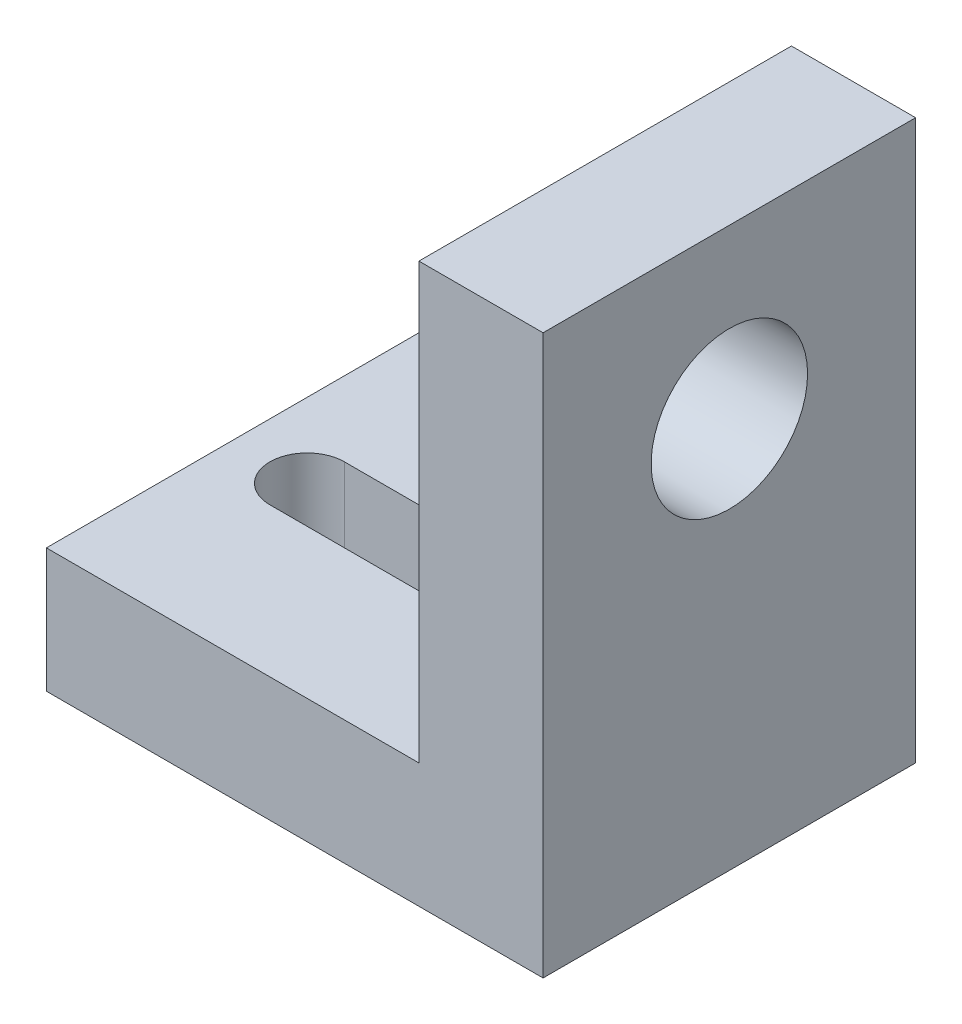
SolidWorks part; units mm, degrees
ref_plane "Front Plane" through (0, 0, 0) normal (0, 0, 1) x (1, 0, 0)
ref_plane "Top Plane" through (0, 0, 0) normal (0, 1, 0) x (1, 0, 0)
ref_plane "Right Plane" through (0, 0, 0) normal (1, 0, 0) x (0, 0, -1)
sketch "Croquis1" plane through (0, 0, 0) normal (0, 1, 0) x (1, 0, 0)
  line L0 (-10, -7.5) -> (10, -7.5)
  line L1 (-10, -7.5) -> (-10, 7.5)
  line L2 (10, -7.5) -> (10, 7.5)
  line L3 (-10, 7.5) -> (10, 7.5)
  line L4 (-10, -7.5) -> (10, 7.5) construction
  line L5 (10, -7.5) -> (-10, 7.5) construction
  point P1 (0, 0)
  dimension "D1" = 20
  dimension "D2" = 15
extrude "Saliente-Extruir1" add sketch "Croquis1" along normal blind 5
sketch "Croquis2" plane through (0, 5, 0) normal (0, 1, 0) x (1, 0, 0)
  line L0 (10, -7.5) -> (5, -7.5)
  line L1 (-10, -7.5) -> (10, -7.5) construction
  line L2 (5, -7.5) -> (5, 7.5)
  line L3 (10, 7.5) -> (-10, 7.5) construction
  line L4 (5, 7.5) -> (10, 7.5)
  line L5 (10, 7.5) -> (10, -7.5)
  dimension "D1" = 5
extrude "Saliente-Extruir2" add sketch "Croquis2" along normal blind 21.5
sketch "Croquis3" plane through (10, 0, 0) normal (1, 0, 0) x (0, 0, -1)
  line L0 (-7.5, 26.5) -> (-7.5, 5) construction
  line L1 (-7.5, 26.5) -> (-7.5, 0) construction
  circle A0 centre (0, 15.75) radius 3.15
  point P4 (-7.5, 15.75)
  dimension "D1" = 6.3
  dimension "D2" = 7.5
extrude "Cortar-Extruir1" cut sketch "Croquis3" against normal blind 20
sketch "Croquis4" plane through (0, 5, 0) normal (0, 1, 0) x (1, 0, 0)
  line L2 (-7, 1.5) -> (2, 1.5)
  line L5 (-10, -7.5) -> (5, -7.5) construction
  line L7 (2, -1.5) -> (-7, -1.5)
  arc A5 (-7, 1.5) -> (-7, -1.5) centre (-7, 0) ccw
  arc A6 (2, -1.5) -> (2, 1.5) centre (2, 0) ccw
  dimension "D1" = 3
  dimension "D2" = 7
  dimension "D4" = 3
  dimension "D3" = 7.5
  dimension "D5" = 7.5
  dimension "D6" = 9
  dimension "D7" = 9
  dimension "D8" = 9
extrude "Cortar-Extruir2" cut sketch "Croquis4" against normal blind 20
sketch "Croquis7" plane through (5, 0, 0) normal (-1, 0, 0) x (0, 0, 1)
  circle A0 centre (0, 15.75) radius 4
  dimension "D1" = 8
extrude "Saliente-Extruir3" add sketch "Croquis7" against normal blind 0.2
sketch "Croquis8" plane through (10, 0, 0) normal (1, 0, 0) x (0, 0, -1)
  line L0 (-7.5, 26.5) -> (-7.5, 22.5)
  line L1 (-7.5, 26.5) -> (-7.5, 0) construction
  line L2 (-7.5, 22.5) -> (7.5, 22.5)
  line L3 (7.5, 26.5) -> (7.5, 0) construction
  line L4 (7.5, 22.5) -> (7.5, 26.5)
  line L5 (7.5, 26.5) -> (-7.5, 26.5)
  dimension "D1" = 4
extrude "Cortar-Extruir3" cut sketch "Croquis8" against normal blind 10
